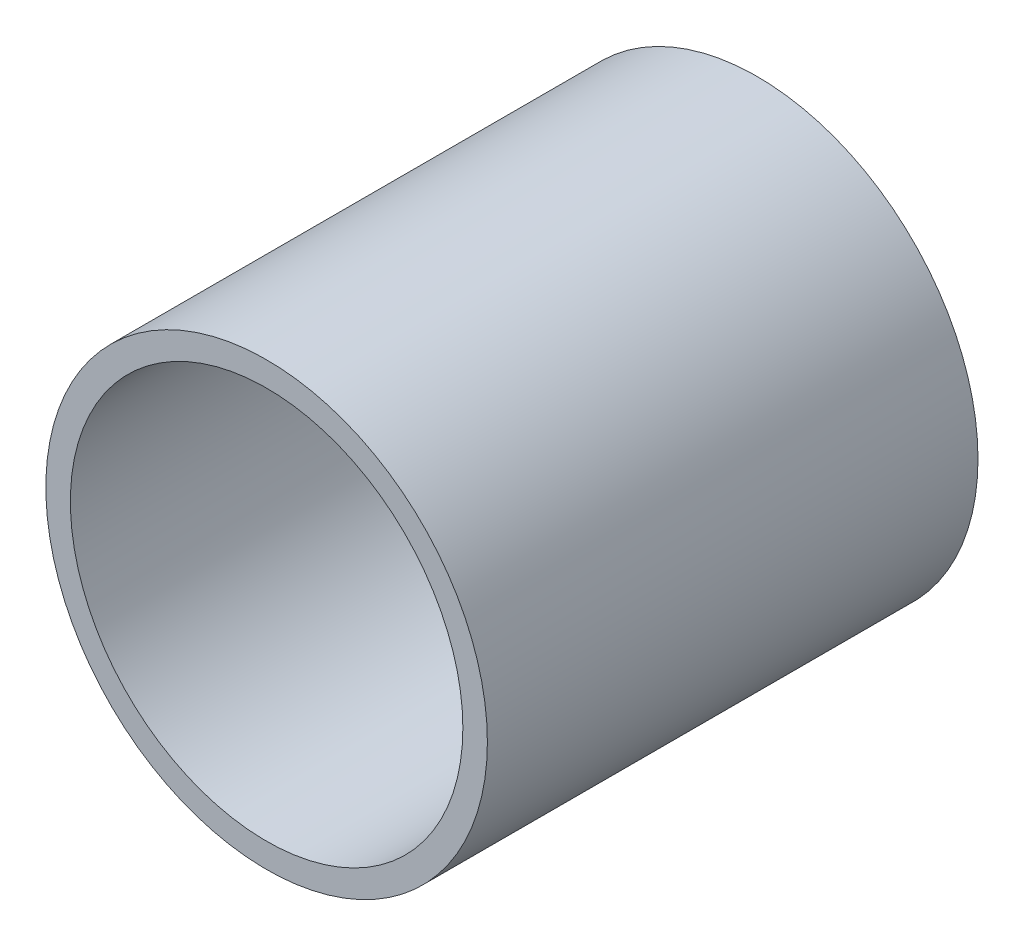
SolidWorks part; units mm, degrees
ref_plane "Ön Düzlem" through (0, 0, 0) normal (0, 0, 1) x (1, 0, 0)
ref_plane "Üst Düzlem" through (0, 0, 0) normal (0, 1, 0) x (1, 0, 0)
ref_plane "Sağ Düzlem" through (0, 0, 0) normal (1, 0, 0) x (0, 0, -1)
sketch "Çizim1" plane through (0, 0, 0) normal (0, 0, 1) x (1, 0, 0)
  circle A0 centre (0, 0) radius 9
  circle A1 centre (0, 0) radius 8
  dimension "D1" = 18
  dimension "D2" = 16
extrude "Yükseklik-Ekstrüzyon1" add sketch "Çizim1" along normal blind 20
